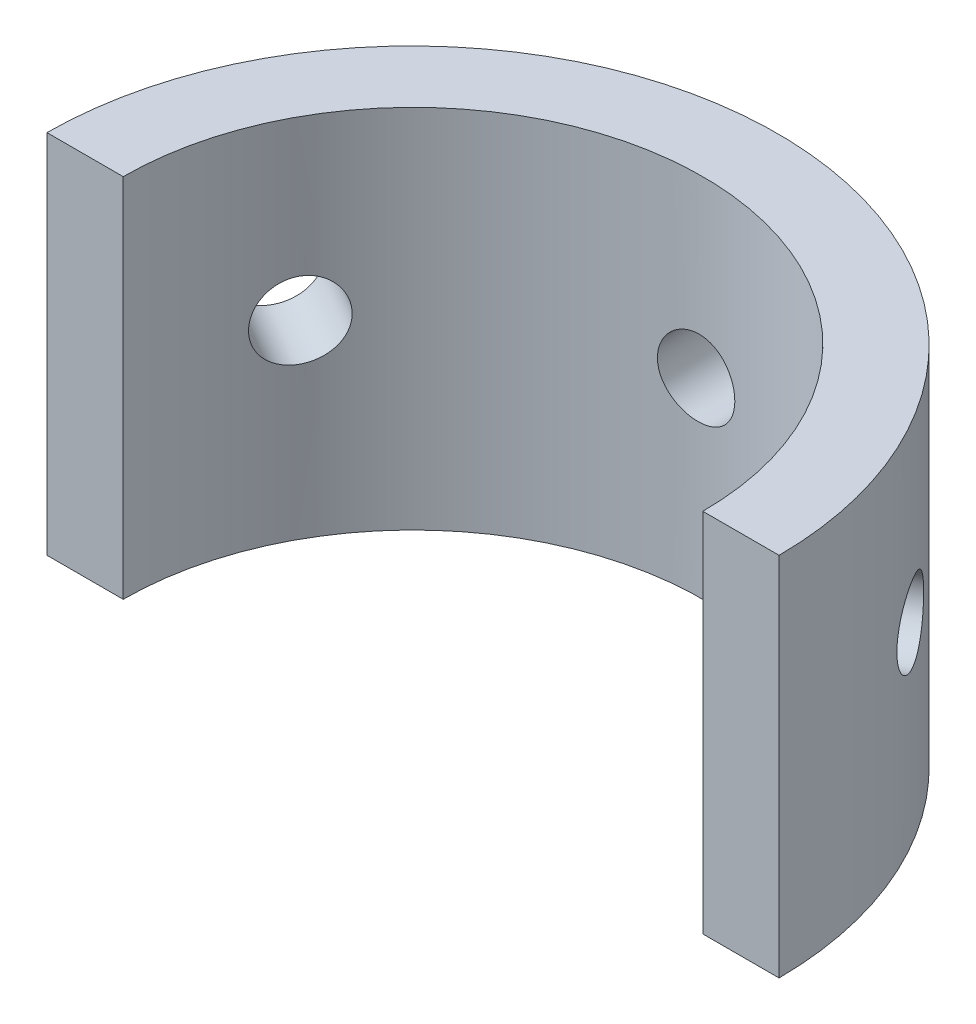
SolidWorks part; units mm, degrees
ref_plane "Front Plane" through (0, 0, 0) normal (0, 0, 1) x (1, 0, 0)
ref_plane "Top Plane" through (0, 0, 0) normal (0, 1, 0) x (1, 0, 0)
ref_plane "Right Plane" through (0, 0, 0) normal (1, 0, 0) x (0, 0, -1)
sketch "Sketch1" plane through (0, 0, 0) normal (0, 1, 0) x (1, 0, 0)
  line L1 (-78.9587, 0) -> (-17.9987, 0)
  arc A0 (-78.9587, 0) -> (-17.9987, 0) centre (-48.4787, -0.1303) cw
  dimension "D1" = 60.96
extrude "Boss-Extrude1" add sketch "Sketch1" along normal blind 30.48 contours L1 A0
ref_plane "Plane1" through (-17.9987, 30.48, 0) normal (1, 0, 0) x (0, 0, -1)
sketch "Sketch3" plane through (0, 0, 0) normal (0, 1, 0) x (1, 0, 0)
  line L0 (-78.9587, 0) -> (-17.9987, 0) construction
  circle A0 centre (-48.4787, 0) radius 24.13
  dimension "D1" = 48.26
extrude "Cut-Extrude4" cut sketch "Sketch3" along normal through all contours A0
sketch "Sketch4" plane through (0, 0, 0) normal (0, 0, 1) x (1, 0, 0)
  circle A0 centre (-48.8244, 15.7989) radius 3.175
  point P2 (0, 0)
  dimension "D1" = 6.35
extrude "Cut-Extrude5" cut sketch "Sketch4" against normal blind 63.754 contours A0
pattern_circular "CirPattern3" count 6 every 60 about axis through (-48.4787, 30.48, 0.1303) along (0, -1, 0) of "Cut-Extrude5"
